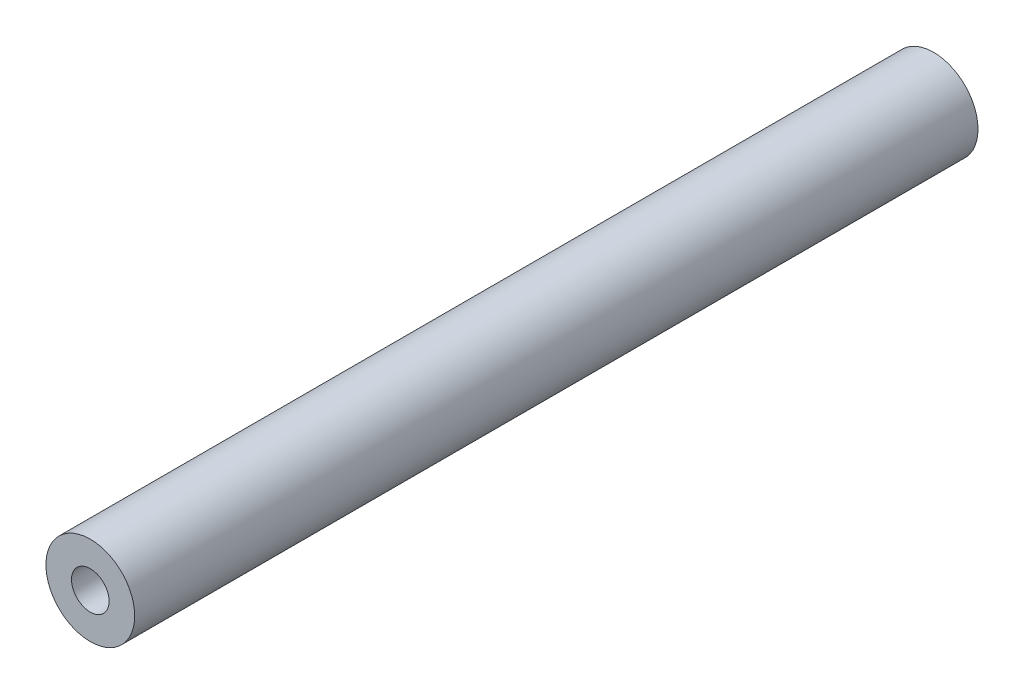
SolidWorks part; units mm, degrees
material "6061-T6 (SS)"
ref_plane "Front Plane" through (0, 0, 0) normal (0, 0, 1) x (1, 0, 0)
ref_plane "Top Plane" through (0, 0, 0) normal (0, 1, 0) x (1, 0, 0)
ref_plane "Right Plane" through (0, 0, 0) normal (1, 0, 0) x (0, 0, -1)
sketch "Sketch1" plane through (0, 0, 0) normal (0, 0, 1) x (1, 0, 0)
  circle A1 centre (0, 0) radius 4.7625
  dimension "D1" = 9.525
extrude "Boss-Extrude1" add sketch "Sketch1" along normal blind 90.4875
hole_wizard "#10-32 Tapped Hole1" positions "3DSketch1" profile "Sketch2" tap size "#10-32" standard "ANSI Inch" end condition through all
sketch3d "3DSketch1"
  line L0 (0, 0, 90.4875) -> (0, 0, 0) construction
  point P0 (0, 0, 90.4875)
  point P4 (0, 0, 0)
sketch "Sketch2" plane through (0, 0, 90.4875) normal (1, 0, 0) x (0, -1, 0)
  line L0 (0, 0) -> (0, 90.4875)
  line L1 (0, 90.4875) -> (2.0193, 90.4875)
  line L2 (2.0193, 90.4875) -> (2.0193, 0)
  line L5 (2.0193, 0) -> (0, 0)
  line L11 (0, -6.35) -> (0, 107.95) construction
  dimension "Thru Tap Drill Dia." = 4.0386
  dimension "Thru Tap Drill Depth" = 90.4875
cosmetic thread "Hole Thread1" parameters "D2"=4.826
cosmetic thread "Hole Thread2" parameters "D2"=4.826
